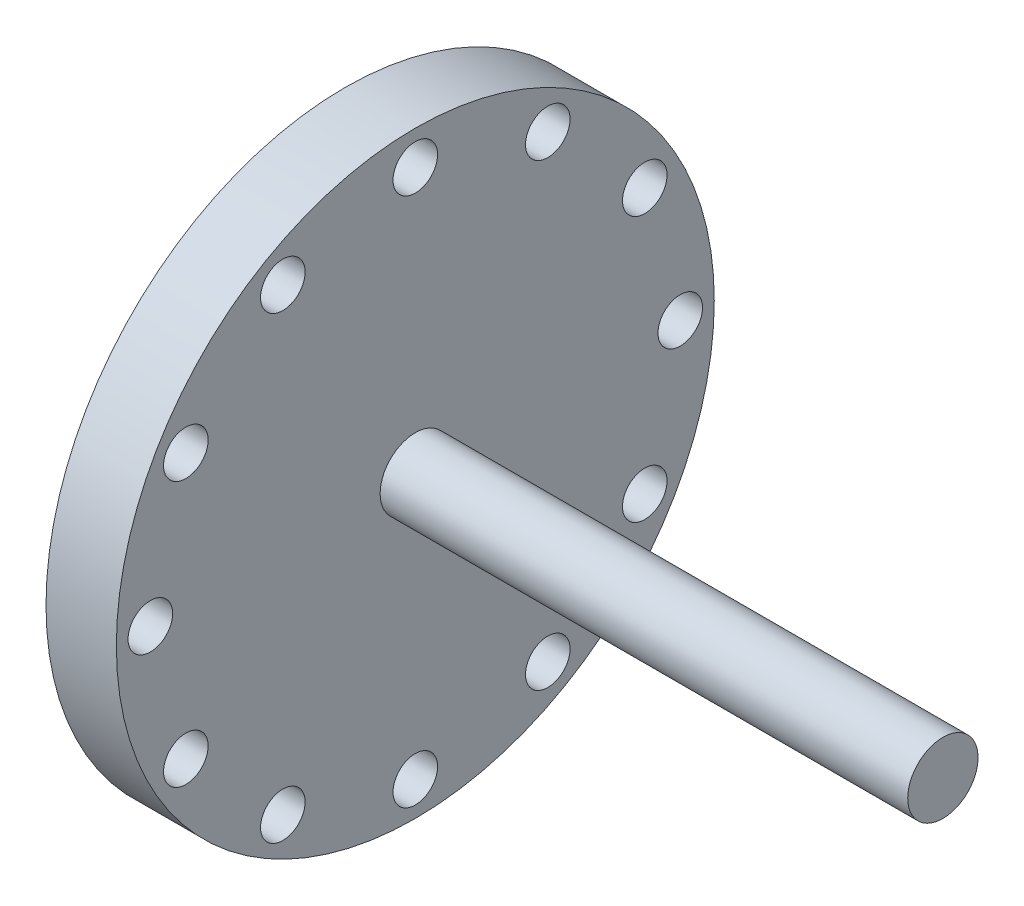
SolidWorks part; units mm, degrees
ref_plane "Спереди" through (0, 0, 0) normal (0, 0, 1) x (1, 0, 0)
ref_plane "Сверху" through (0, 0, 0) normal (0, 1, 0) x (1, 0, 0)
ref_plane "Справа" through (0, 0, 0) normal (1, 0, 0) x (0, 0, -1)
sketch "Эскиз1" plane through (0, 0, 0) normal (0, 0, 1) x (1, 0, 0)
  line L0 (0, 0) -> (265, 0)
  line L1 (0, 0) -> (0, 20)
  line L2 (0, 20) -> (10, 20)
  line L3 (10, 20) -> (10, 127.5)
  line L4 (10, 127.5) -> (40, 127.5)
  line L5 (40, 127.5) -> (40, 15)
  line L6 (40, 15) -> (265, 15)
  line L7 (265, 0) -> (265, 15)
revolve "Повернуть1" add sketch "Эскиз1" angle 360 about L0
sketch "Эскиз2" plane through (0, 0, 0) normal (1, 0, 0) x (0, 0, -1)
  circle A0 centre (0, 113) radius 9.5
extrude "Вырез-Вытянуть1" cut sketch "Эскиз2" along normal through all
sketch "Эскиз3" plane through (0, 0, 0) normal (1, 0, 0) x (0, 0, -1)
  circle A0 centre (-56.5, 97.8609) radius 9.5
extrude "Вырез-Вытянуть2" cut sketch "Эскиз3" along normal through all
sketch "Эскиз4" plane through (0, 0, 0) normal (1, 0, 0) x (0, 0, -1)
  circle A0 centre (-97.8609, 56.5) radius 9.5
extrude "Вырез-Вытянуть3" cut sketch "Эскиз4" along normal through all
sketch "Эскиз5" plane through (0, 0, 0) normal (1, 0, 0) x (0, 0, -1)
  circle A0 centre (-113, 0) radius 9.5
extrude "Вырез-Вытянуть4" cut sketch "Эскиз5" along normal through all
sketch "Эскиз6" plane through (0, 0, 0) normal (1, 0, 0) x (0, 0, -1)
  circle A0 centre (-97.8609, -56.5) radius 9.5
extrude "Вырез-Вытянуть5" cut sketch "Эскиз6" along normal through all
sketch "Эскиз7" plane through (0, 0, 0) normal (1, 0, 0) x (0, 0, -1)
  circle A0 centre (-56.5, -97.8609) radius 9.5
extrude "Вырез-Вытянуть6" cut sketch "Эскиз7" along normal through all
sketch "Эскиз8" plane through (0, 0, 0) normal (1, 0, 0) x (0, 0, -1)
  circle A0 centre (0, -113) radius 9.5
extrude "Вырез-Вытянуть7" cut sketch "Эскиз8" along normal through all
sketch "Эскиз9" plane through (0, 0, 0) normal (1, 0, 0) x (0, 0, -1)
  circle A0 centre (56.5, -97.8609) radius 9.5
extrude "Вырез-Вытянуть8" cut sketch "Эскиз9" along normal through all
sketch "Эскиз10" plane through (0, 0, 0) normal (1, 0, 0) x (0, 0, -1)
  circle A0 centre (97.8609, -56.5) radius 9.5
extrude "Вырез-Вытянуть9" cut sketch "Эскиз10" along normal through all
sketch "Эскиз11" plane through (0, 0, 0) normal (1, 0, 0) x (0, 0, -1)
  circle A0 centre (113, 0) radius 9.5
extrude "Вырез-Вытянуть10" cut sketch "Эскиз11" along normal through all
sketch "Эскиз12" plane through (0, 0, 0) normal (1, 0, 0) x (0, 0, -1)
  circle A0 centre (97.8609, 56.5) radius 9.5
extrude "Вырез-Вытянуть11" cut sketch "Эскиз12" along normal through all
sketch "Эскиз13" plane through (0, 0, 0) normal (1, 0, 0) x (0, 0, -1)
  circle A0 centre (56.5, 97.8609) radius 9.5
extrude "Вырез-Вытянуть12" cut sketch "Эскиз13" along normal through all
